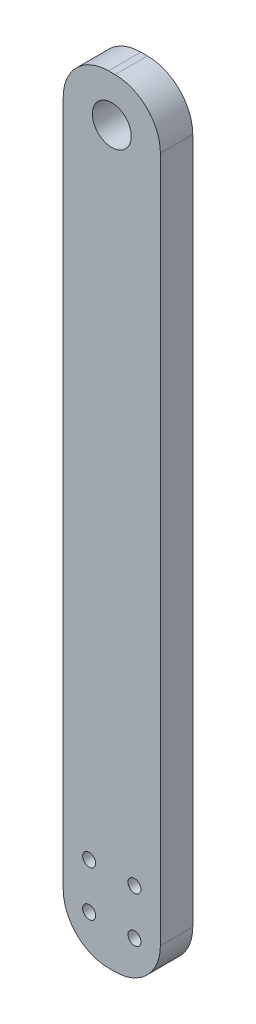
SolidWorks part; units mm, degrees
ref_plane "Front Plane" through (0, 0, 0) normal (0, 0, 1) x (1, 0, 0)
ref_plane "Top Plane" through (0, 0, 0) normal (0, 1, 0) x (1, 0, 0)
ref_plane "Right Plane" through (0, 0, 0) normal (1, 0, 0) x (0, 0, -1)
sketch "Sketch1" plane through (0, 0, 0) normal (0, 0, 1) x (1, 0, 0)
  line L1 (0, 0) -> (9, 0)
  line L2 (0, 0) -> (0, 9)
  line L3 (0, 9) -> (9, 9)
  line L4 (9, 0) -> (9, 9)
  line L5 (9, 9) -> (7, 9)
  line L6 (9, 9) -> (9, 7)
  line L7 (9, 7) -> (7, 7)
  line L8 (7, 9) -> (7, 7)
  line L9 (9, 0) -> (7, 0)
  line L10 (9, 0) -> (9, 2)
  line L11 (9, 2) -> (7, 2)
  line L12 (7, 0) -> (7, 2)
  line L13 (0, 0) -> (2, 0)
  line L14 (0, 0) -> (0, 2)
  line L15 (0, 2) -> (2, 2)
  line L16 (2, 0) -> (2, 2)
  line L17 (0, 9) -> (2, 9)
  line L18 (0, 9) -> (0, 7)
  line L19 (0, 7) -> (2, 7)
  line L20 (2, 9) -> (2, 7)
  circle A0 centre (8, 1) radius 1
  circle A1 centre (1, 1) radius 1
  circle A2 centre (1, 8) radius 1
  circle A3 centre (8, 8) radius 1
  dimension "D11" = 2
  dimension "D12" = 2
  dimension "D13" = 2
  dimension "D14" = 2
  dimension "D1" = 2
  dimension "D2" = 2
  dimension "D3" = 2
  dimension "D4" = 2
  dimension "D5" = 2
  dimension "D6" = 2
  dimension "D7" = 2
  dimension "D8" = 2
  dimension "D9" = 9
  dimension "D10" = 9
  dimension "D15" = 1
  dimension "D16" = 1
  dimension "D17" = 1
  dimension "D18" = 1
extrude "Boss-Extrude1" add sketch "Sketch1" along normal blind 5 contours A0 | A3 | A2 | A1
sketch "Sketch2" plane through (0, 0, 5) normal (0, 0, 1) x (1, 0, 0)
  line L1 (4, -5) -> (5, -5)
  line L2 (-3, 2) -> (-3, 108)
  line L3 (4, 115) -> (5, 115)
  line L4 (12, 2) -> (12, 108)
  line L6 (4, 108) -> (5, 108)
  line L8 (4, 108) -> (5, 108)
  arc A0 (4, 115) -> (-3, 108) centre (4, 108) ccw
  arc A1 (5, 115) -> (12, 108) centre (5, 108) cw
  arc A2 (5, -5) -> (12, 2) centre (5, 2) ccw
  arc A3 (4, -5) -> (-3, 2) centre (4, 2) cw
  circle A4 centre (4.5, 108) radius 3
  circle A5 centre (1, 1) radius 1 construction
  circle A6 centre (8, 1) radius 1 construction
  point P12 (12, 115)
  point P15 (12, -5)
  dimension "D5" = 7
  dimension "D6" = 6
  dimension "D4" = 3
  dimension "D1" = 120
  dimension "D2" = 6
  dimension "D3" = 15
extrude "Boss-Extrude2" add sketch "Sketch2" along normal blind 5
sketch "Sketch3" plane through (0, 0, 0) normal (0, 0, -1) x (-1, 0, 0)
  circle A0 centre (-8, 8) radius 1
  circle A1 centre (-1, 8) radius 1
  circle A2 centre (-1, 1) radius 1
  circle A3 centre (-8, 1) radius 1
extrude "Cut-Extrude2" cut sketch "Sketch3" against normal blind 10
